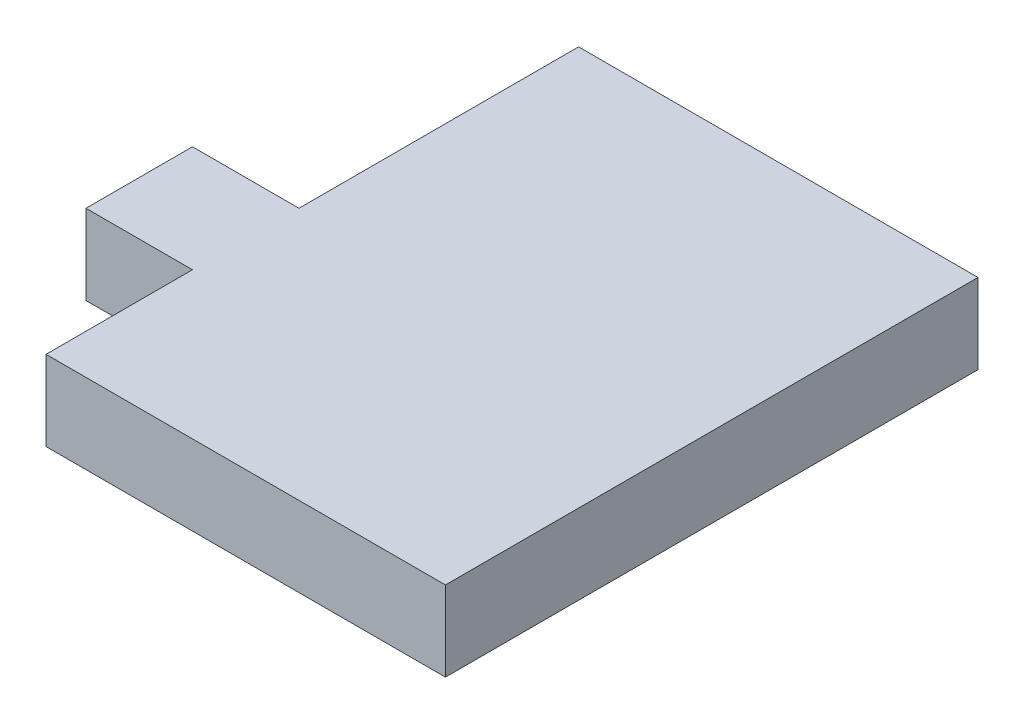
SolidWorks part; units mm, degrees
ref_plane "Front Plane" through (0, 0, 0) normal (0, 0, 1) x (1, 0, 0)
ref_plane "Top Plane" through (0, 0, 0) normal (0, 1, 0) x (1, 0, 0)
ref_plane "Right Plane" through (0, 0, 0) normal (1, 0, 0) x (0, 0, -1)
sketch "Sketch1" plane through (0, 0, 0) normal (0, 1, 0) x (1, 0, 0)
  line L1 (0, 2) -> (-1.5, 2)
  line L2 (-1.5, 2) -> (-1.5, 0.95)
  line L3 (-1.5, 0.95) -> (-1.9, 0.95)
  line L4 (-1.9, 0.95) -> (-1.9, 0.55)
  line L5 (-1.9, 0.55) -> (-1.5, 0.55)
  line L6 (-1.5, 0.55) -> (-1.5, 0)
  line L7 (-1.5, 0) -> (0, 0)
  line L8 (0, 2) -> (0, 0)
  dimension "D1" = 1.5
  dimension "D2" = 2
  dimension "D3" = 0.4
  dimension "D4" = 0.4
  dimension "D5" = 0.55
extrude "Boss-Extrude1" add sketch "Sketch1" along normal blind 0.3
equation "\"t\"= 0.3'thickness of the sheets"
equation "\"FlexJoint\"= 0.15'Width of flextures"
equation "\"FoldJoint\"= 0.4'Width of folding joints"
equation "\"AssembleAngle\"= 90'Angle of assembly parts"
equation "\"D1@Boss-Extrude1\"=\"t\""
